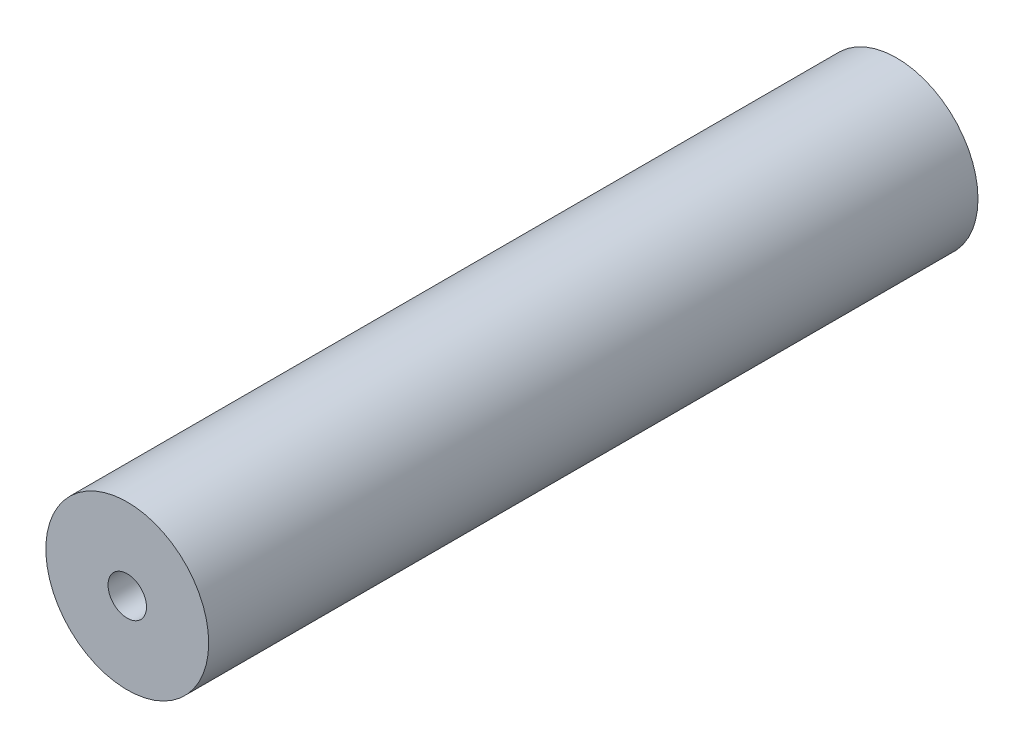
SolidWorks part; units mm, degrees
ref_plane "Front Plane" through (0, 0, 0) normal (0, 0, 1) x (1, 0, 0)
ref_plane "Top Plane" through (0, 0, 0) normal (0, 1, 0) x (1, 0, 0)
ref_plane "Right Plane" through (0, 0, 0) normal (1, 0, 0) x (0, 0, -1)
sketch "Sketch1" plane through (0, 0, 0) normal (0, 0, 1) x (1, 0, 0)
  circle A0 centre (0, 0) radius 3.175
  circle A1 centre (0, 0) radius 0.75
extrude "Boss-Extrude1" add sketch "Sketch1" along normal blind 30
